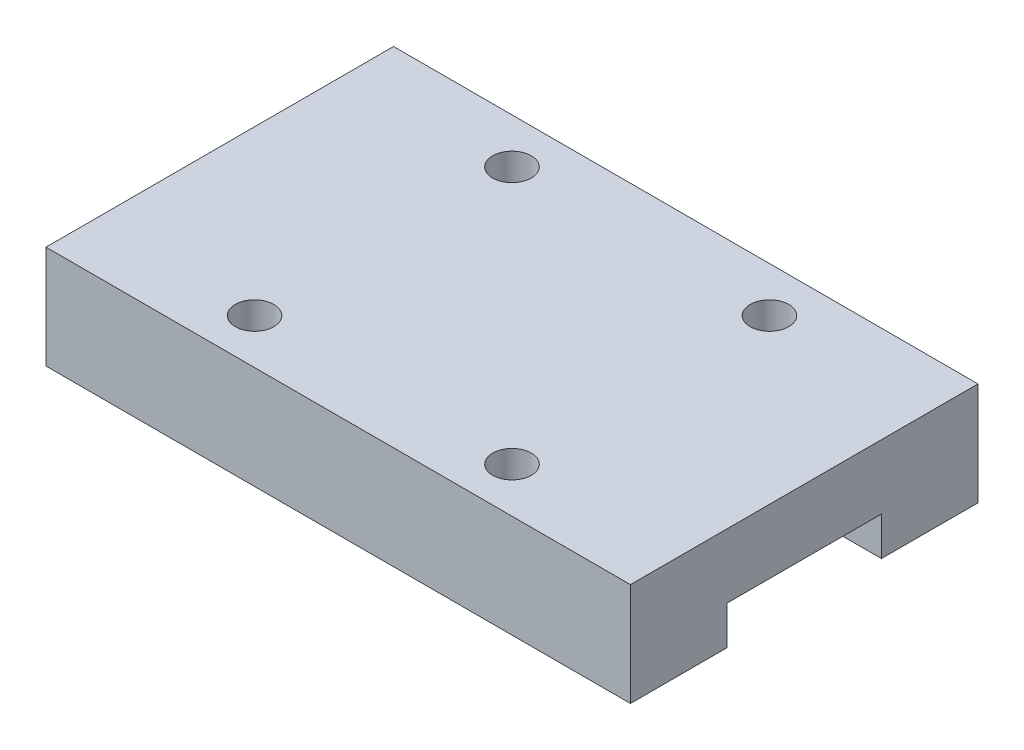
SolidWorks part; units mm, degrees
material "1023 Carbon Steel Sheet (SS)"
ref_plane "Front Plane" through (0, 0, 0) normal (0, 0, 1) x (1, 0, 0)
ref_plane "Top Plane" through (0, 0, 0) normal (0, 1, 0) x (1, 0, 0)
ref_plane "Right Plane" through (0, 0, 0) normal (1, 0, 0) x (0, 0, -1)
sketch "Sketch1" plane through (0, 0, 0) normal (0, 1, 0) x (1, 0, 0)
  line L1 (22.7, 13.5) -> (-22.7, 13.5)
  line L2 (22.7, 13.5) -> (22.7, -13.5)
  line L3 (22.7, -13.5) -> (-22.7, -13.5)
  line L4 (-22.7, 13.5) -> (-22.7, -13.5)
  line L5 (22.7, 13.5) -> (-22.7, -13.5) construction
  line L6 (22.7, -13.5) -> (-22.7, 13.5) construction
  point P0 (0, 0)
  dimension "D1" = 45.4
  dimension "D2" = 27
extrude "Boss-Extrude1" add sketch "Sketch1" along normal blind 8
sketch "Sketch2" plane through (22.7, 0, 0) normal (1, 0, 0) x (0, 0, -1)
  line L0 (-13.5, 0) -> (13.5, 0) construction
  line L1 (-6, 0) -> (6, 0)
  line L2 (-6, 0) -> (-6, 3)
  line L3 (-6, 3) -> (6, 3)
  line L4 (6, 0) -> (6, 3)
  line L5 (13.5, 8) -> (13.5, 0) construction
  line L6 (-13.5, 8) -> (-13.5, 0) construction
  line L7 (-13.5, 8) -> (13.5, 8) construction
  dimension "D1" = 12
  dimension "D2" = 7.5
  dimension "D3" = 7.5
  dimension "D4" = 7.5
  dimension "D5" = 5
extrude "Cut-Extrude1" cut sketch "Sketch2" against normal through all
sketch "Sketch3" plane through (0, 8, 0) normal (0, 1, 0) x (1, 0, 0)
  line L0 (-22.7, -13.5) -> (22.7, -13.5) construction
  line L1 (22.7, 13.5) -> (-22.7, 13.5) construction
  line L2 (22.7, -13.5) -> (22.7, 13.5) construction
  line L3 (-22.7, 13.5) -> (-22.7, -13.5) construction
  circle A0 centre (10, -10) radius 1.5
  circle A1 centre (-10, -10) radius 1.5
  circle A2 centre (-10, 10) radius 1.5
  circle A3 centre (10, 10) radius 1.5
  dimension "D3" = 3
  dimension "D4" = 3.5
  dimension "D5" = 3.5
  dimension "D6" = 12.7
  dimension "D7" = 12.7
  dimension "D1" = 20
  dimension "D2" = 20
extrude "Cut-Extrude2" cut sketch "Sketch3" against normal blind 10
